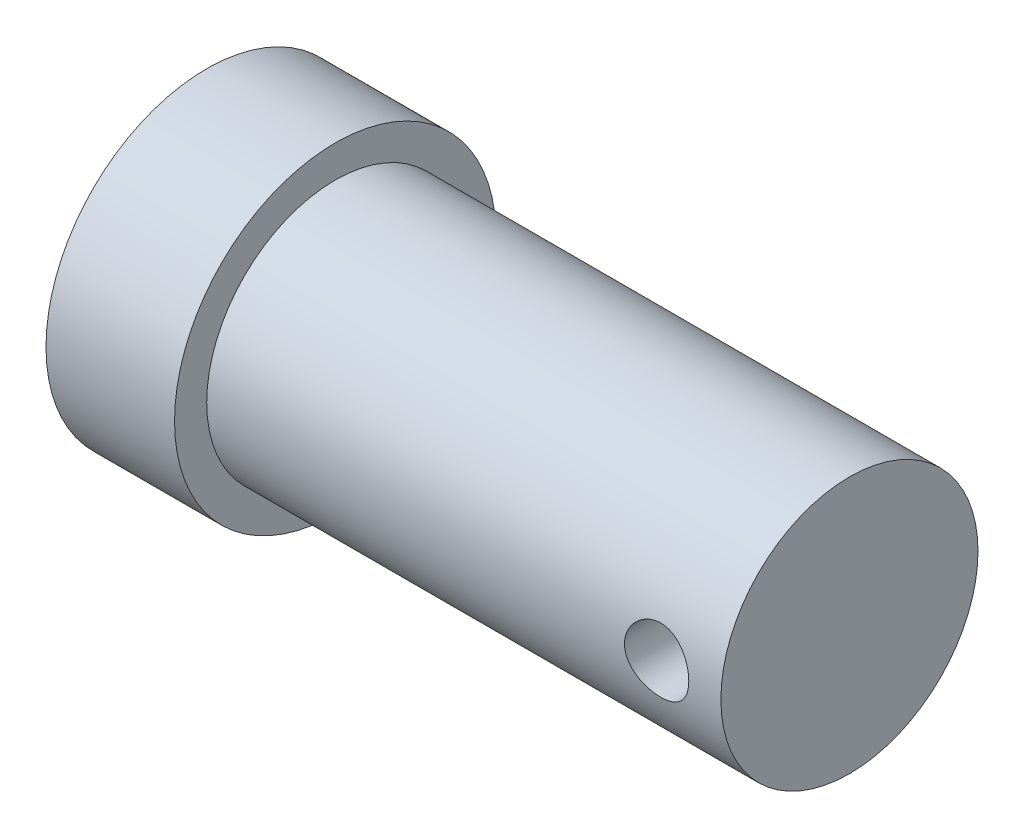
SolidWorks part; units mm, degrees
material "AISI 1045 Çelik, soğuk çekilmiş"
ref_plane "Ön Düzlem" through (0, 0, 0) normal (0, 0, 1) x (1, 0, 0)
ref_plane "Üst Düzlem" through (0, 0, 0) normal (0, 1, 0) x (1, 0, 0)
ref_plane "Sağ Düzlem" through (0, 0, 0) normal (1, 0, 0) x (0, 0, -1)
sketch "Çizim1" plane through (0, 0, 0) normal (0, 0, 1) x (1, 0, 0)
  line L0 (0, 0) -> (100, 0) construction
  line L1 (0, 0) -> (0, 25)
  line L2 (0, 25) -> (20, 25)
  line L3 (20, 25) -> (20, 20)
  line L4 (20, 20) -> (100, 20)
  line L5 (100, 20) -> (100, 0)
  line L6 (0, 0) -> (100, 0)
  dimension "D1" = 100
  dimension "D2" = 20
  dimension "D3" = 5
  dimension "D4" = 20
revolve "Döndür1" add sketch "Çizim1" angle 360 about L0
sketch "Çizim2" plane through (0, 0, 0) normal (0, 0, 1) x (1, 0, 0)
  line L0 (100, -20) -> (100, 20) construction
  circle A0 centre (90, 0) radius 5
  dimension "D1" = 10
  dimension "D2" = 10
extrude "Kes-Ekstrüzyon1" cut sketch "Çizim2" against normal mid plane 40
